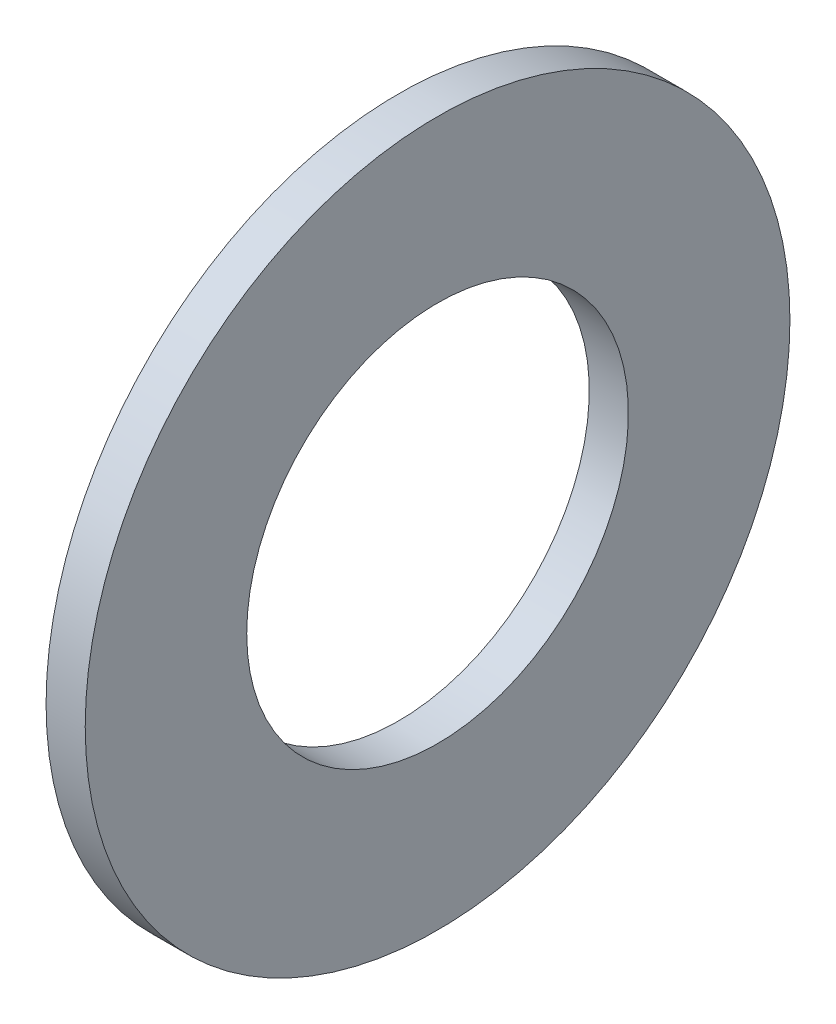
SolidWorks part; units mm, degrees
ref_plane "Plane1" through (0, 0, 0) normal (0, 0, 1) x (1, 0, 0)
ref_plane "Plane2" through (0, 0, 0) normal (0, 1, 0) x (1, 0, 0)
ref_plane "Plane3" through (0, 0, 0) normal (1, 0, 0) x (0, 0, -1)
sketch "Sketch1" plane through (0, 0, 0) normal (0, 0, 1) x (1, 0, 0)
  line L0 (-34.925, 0) -> (9.525, 0) construction
  line L1 (0, 19.5) -> (0, 36)
  line L2 (0, 36) -> (-4, 36)
  line L3 (-4, 36) -> (-4, 19.5)
  line L4 (-4, 19.5) -> (0, 19.5)
  dimension "Thickness" = 4
  dimension "Inside_dia" = 39
  dimension "Outside_dia" = 72
revolve "Base-Revolve" add sketch "Sketch1" angle 360 about L0
